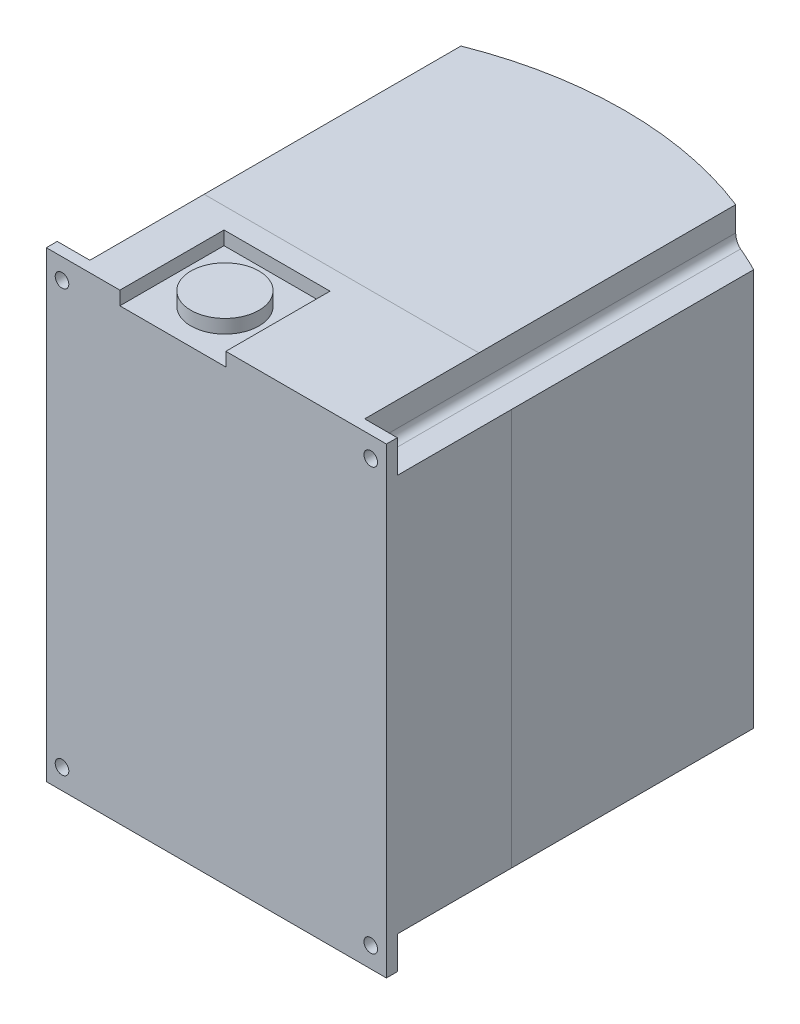
SolidWorks part; units mm, degrees
ref_plane "Front Plane" through (0, 0, 0) normal (0, 0, 1) x (1, 0, 0)
ref_plane "Top Plane" through (0, 0, 0) normal (0, 1, 0) x (1, 0, 0)
ref_plane "Right Plane" through (0, 0, 0) normal (1, 0, 0) x (0, 0, -1)
sketch "Sketch1" plane through (0, 0, 0) normal (1, 0, 0) x (0, 0, -1)
  line L1 (-75, -85) -> (75, -85)
  line L2 (-75, -85) -> (-75, 85)
  line L3 (-75, 85) -> (75, 85)
  line L4 (75, -85) -> (75, 85)
  line L5 (-75, -85) -> (75, 85) construction
  line L6 (-75, 85) -> (75, -85) construction
  point P0 (0, 0)
  dimension "D1" = 170
  dimension "D2" = 150
extrude "Boss-Extrude1" add sketch "Sketch1" along normal mid plane 125
sketch "Sketch2" plane through (0, 85, 0) normal (0, 1, 0) x (1, 0, 0)
  line L0 (-62.5, 75) -> (-62.5, -75) construction
  line L1 (62.5, 75) -> (62.5, -75) construction
  line L2 (62.5, -75) -> (-62.5, -75) construction
  line L3 (0, 0) -> (0, 147.7344) construction
  line L4 (62.5, 75) -> (-62.5, 75) construction
  arc A0 (-62.5, 60) -> (62.5, 60) centre (0, -62.7083) cw
  dimension "D1" = 135
extrude "Cut-Extrude1" cut sketch "Sketch2" against normal through all and the other way through all
sketch "Sketch3" plane through (0, 0, 75) normal (0, 0, 1) x (1, 0, 0)
  line L0 (0, 0) -> (0, 125.871) construction
  line L1 (50.5, 125.1382) -> (106.6216, 125.1382)
  line L2 (50.5, 125.1382) -> (50.5, 76)
  line L3 (53.5, 73) -> (106.6216, 73)
  line L4 (106.6216, 125.1382) -> (106.6216, 73)
  line L5 (50.5, 125.1382) -> (106.6216, 73) construction
  line L6 (50.5, 73) -> (106.6216, 125.1382) construction
  line L7 (0, 0) -> (94.5521, 0) construction
  line L8 (62.5, 85) -> (-62.5, 85) construction
  line L9 (62.5, 85) -> (62.5, -85) construction
  line L10 (-50.5, 73) -> (-106.6216, 125.1382) construction
  line L11 (-50.5, 125.1382) -> (-106.6216, 73) construction
  line L12 (-106.6216, 125.1382) -> (-106.6216, 73)
  line L13 (-53.5, 73) -> (-106.6216, 73)
  line L14 (-50.5, 125.1382) -> (-50.5, 76)
  line L15 (-50.5, 125.1382) -> (-106.6216, 125.1382)
  line L16 (-50.5, -125.1382) -> (-106.6216, -73) construction
  line L17 (-50.5, -73) -> (-106.6216, -125.1382) construction
  line L18 (50.5, -73) -> (106.6216, -125.1382) construction
  line L19 (50.5, -125.1382) -> (106.6216, -73) construction
  line L20 (-50.5, -125.1382) -> (-106.6216, -125.1382)
  line L21 (-50.5, -125.1382) -> (-50.5, -76)
  line L22 (-53.5, -73) -> (-106.6216, -73)
  line L23 (-106.6216, -125.1382) -> (-106.6216, -73)
  line L24 (106.6216, -125.1382) -> (106.6216, -73)
  line L25 (53.5, -73) -> (106.6216, -73)
  line L26 (50.5, -125.1382) -> (50.5, -76)
  line L27 (50.5, -125.1382) -> (106.6216, -125.1382)
  arc A0 (50.5, 76) -> (53.5, 73) centre (53.5, 76) ccw
  arc A1 (-50.5, 76) -> (-53.5, 73) centre (-53.5, 76) cw
  arc A2 (-50.5, -76) -> (-53.5, -73) centre (-53.5, -76) ccw
  arc A3 (50.5, -76) -> (53.5, -73) centre (53.5, -76) cw
  point P0 (78.5608, 99.0691)
  point P23 (-78.5608, 99.0691)
  point P38 (-78.5608, -99.0691)
  point P39 (78.5608, -99.0691)
  dimension "D3" = 3
  dimension "D1" = 12
  dimension "D2" = 12
extrude "Cut-Extrude2" cut sketch "Sketch3" against normal through all from offset 4 offset against normal yes
sketch "Sketch4" plane through (0, 0, 71) normal (0, 0, -1) x (-1, 0, 0)
  line L0 (0, 0) -> (-92.4867, 0) construction
  line L1 (0, 0) -> (0, 113.9489) construction
  circle A0 centre (-56.75, 77.5) radius 2.5
  circle A1 centre (56.75, 77.5) radius 2.5
  circle A2 centre (56.75, -77.5) radius 2.5
  circle A3 centre (-56.75, -77.5) radius 2.5
  dimension "D1" = 5
  dimension "D2" = 108.5
  dimension "D3" = 150
extrude "Cut-Extrude3" cut sketch "Sketch4" against normal through all
sketch "Sketch5" plane through (0, 0, 0) normal (0, 0, 1) x (1, 0, 0)
  line L0 (50.5, 85) -> (-50.5, 85) construction
  line L1 (27.5, 67) -> (-27.5, 67)
  line L2 (27.5, 67) -> (27.5, -9)
  line L3 (27.5, -9) -> (-27.5, -9)
  line L4 (-27.5, 67) -> (-27.5, -9)
  line L5 (27.5, 67) -> (-27.5, -9) construction
  line L6 (27.5, -9) -> (-27.5, 67) construction
  point P0 (0, 29)
  dimension "D1" = 18
  dimension "D2" = 55
  dimension "D3" = 76
split line "Split Line1"
sketch "Sketch6" plane through (0, 0, 0) normal (0, 0, 1) x (1, 0, 0)
  line L0 (50.5, 85) -> (-50.5, 85) construction
  line L1 (-62.5, 73) -> (-62.5, -73) construction
  circle A0 centre (-16.5, 25) radius 5
  dimension "D1" = 10
  dimension "D2" = 60
  dimension "D3" = 46
extrude "Boss-Extrude2" [suppressed] add sketch "Sketch6" against normal offset from surface (84.5516 mm away) 10
sketch "Sketch7" plane through (0, 85, 0) normal (0, 1, 0) x (1, 0, 0)
  line L0 (62.5, -75) -> (-62.5, -75) construction
  line L1 (-35.4755, -36.7093) -> (3.4809, -36.7093)
  line L2 (-35.4755, -36.7093) -> (-35.4755, -75)
  line L3 (-35.4755, -75) -> (3.4809, -75)
  line L4 (3.4809, -36.7093) -> (3.4809, -75)
  line L5 (-35.4755, -36.7093) -> (3.4809, -75) construction
  line L6 (-35.4755, -75) -> (3.4809, -36.7093) construction
  circle A0 centre (-15.9973, -55.8547) radius 12.5199
  point P0 (-15.9973, -55.8547)
  point P9 (-17.4966, -54.2622)
  point P10 (-27.5591, -55.8547)
extrude "Cut-Extrude4" cut sketch "Sketch7" against normal blind 5
sketch "Sketch8" plane through (-62.5, 0, 0) normal (-1, 0, 0) x (0, 0, 1)
  line L0 (29, -109.9316) -> (29, 157.0624)
  line L1 (75, 85) -> (75, -85) construction
  dimension "D1" = 46
split line "Split Line2"
